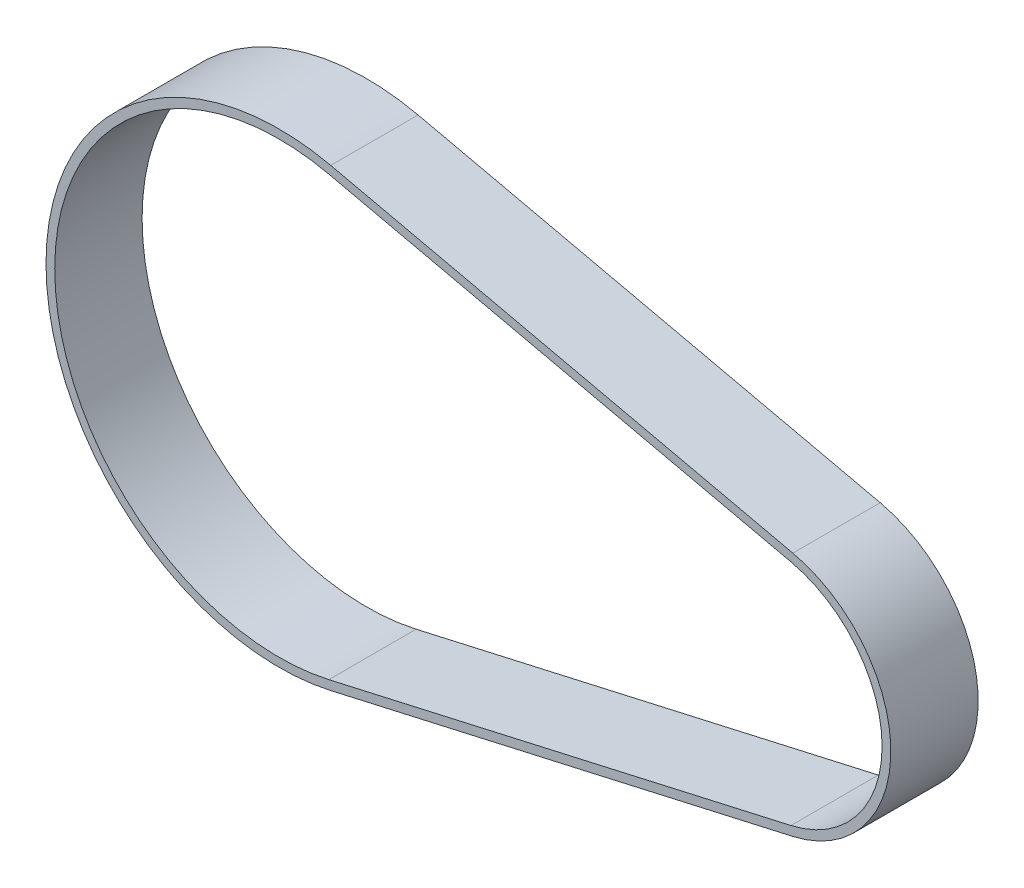
SolidWorks part; units mm, degrees
ref_plane "Front Plane" through (0, 0, 0) normal (0, 0, 1) x (1, 0, 0)
ref_plane "Top Plane" through (0, 0, 0) normal (0, 1, 0) x (1, 0, 0)
ref_plane "Right Plane" through (0, 0, 0) normal (1, 0, 0) x (0, 0, -1)
sketch "Sketch1" plane through (0, 0, 0) normal (0, 0, 1) x (1, 0, 0)
  line L0 (5.6796, 25.0574) -> (58.5782, 13.0672)
  line L1 (58.5782, -13.0672) -> (5.6796, -25.0574)
  line L2 (5.9007, 26.0326) -> (58.7992, 14.0424)
  line L3 (58.7992, -14.0424) -> (5.9007, -26.0326)
  arc A0 (58.5782, 13.0672) -> (58.5782, -13.0672) centre (55.6163, 0) cw
  arc A1 (5.6796, -25.0574) -> (5.6796, 25.0574) centre (0, 0) cw
  arc A2 (58.7992, 14.0424) -> (58.7992, -14.0424) centre (55.6163, 0) cw
  arc A3 (5.9007, -26.0326) -> (5.9007, 26.0326) centre (0, 0) cw
  dimension "D2" = 1
  dimension "D4" = 13.3986
  dimension "D3" = 25.693
  dimension "D1" = 55.6163
extrude "Boss-Extrude1" add sketch "Sketch1" along normal blind 10
